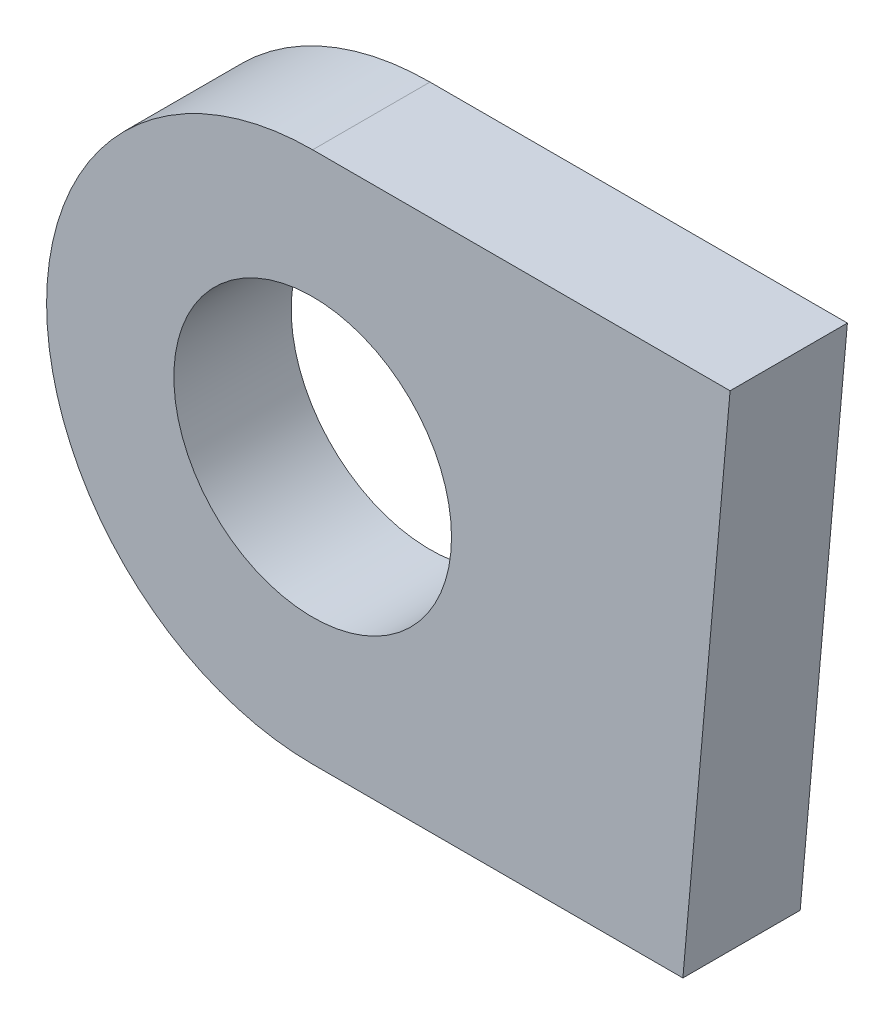
SolidWorks part; units mm, degrees
ref_plane "Front Plane" through (0, 0, 0) normal (1, 0, 0) x (0, 1, 0)
ref_plane "Top Plane" through (0, 0, 0) normal (0, 0, 1) x (0, 1, 0)
ref_plane "Right Plane" through (0, 0, 0) normal (0, 1, 0) x (-1, 0, 0)
sketch "Sketch1" plane through (0, 0, 0) normal (0, 0, 1) x (0, 1, 0)
  line L0 (-11.5, 0) -> (-11.5, -16)
  line L1 (-11.5, -16) -> (11.5, -18.0406)
  line L2 (11.5, 0) -> (11.5, -18.0406)
  line L3 (-15.2019, -16) -> (-50015.2019, -16) construction
  circle A0 centre (0, 0) radius 6
  arc A1 (11.5, 0) -> (-11.5, 0) centre (0, 0) ccw
  arc A2 (-11.5, 0) -> (11.5, 0) centre (0, 0) ccw
  point P3 (0, 0)
  point P8 (11.2749, -6.0387)
  point P12 (13.9927, 1.6501)
  dimension "D2" = 12
  dimension "D3" = 11.5
  dimension "D1" = 5.07
  dimension "D4" = 16
extrude "Boss-Extrude1" add sketch "Sketch1" along normal mid plane 5.07 contours L3 L2 A2 L0 | A1 A2 A0 | L2 L3 L1
